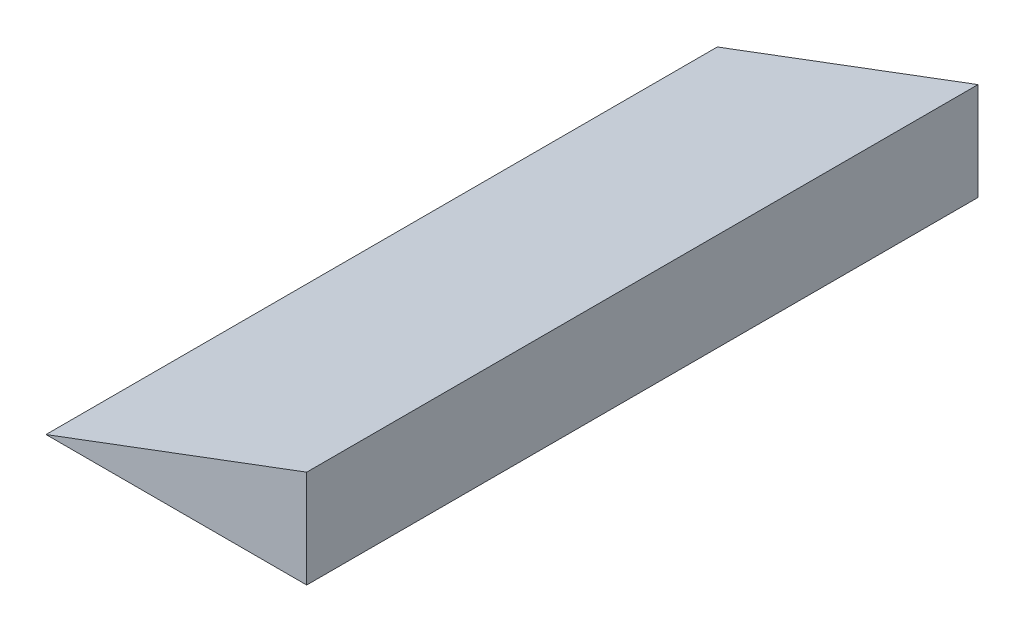
SolidWorks part; units mm, degrees
ref_plane "Front Plane" through (0, 0, 0) normal (0, 0, 1) x (1, 0, 0)
ref_plane "Top Plane" through (0, 0, 0) normal (0, 1, 0) x (1, 0, 0)
ref_plane "Right Plane" through (0, 0, 0) normal (1, 0, 0) x (0, 0, -1)
sketch "Sketch1" plane through (0, 0, 0) normal (0, 0, 1) x (1, 0, 0)
  line L0 (12, 15) -> (-28, 0)
  line L1 (-28, 0) -> (12, 0)
  line L2 (12, 0) -> (12, 15)
  dimension "D1" = 15
  dimension "D2" = 40
  dimension "D3" = 0
  dimension "D4" = 12
extrude "Boss-Extrude1" add sketch "Sketch1" along normal blind 103
sketch "Sketch2" plane through (0, 0, 0) normal (0, -1, 0) x (1, 0, 0)
  line L0 (-28, 103) -> (12, 103) construction
  line L1 (-15, 103) -> (0, 103)
  line L2 (-15, 103) -> (-15, 0)
  line L3 (-15, 0) -> (0, 0)
  line L4 (0, 103) -> (0, 0)
  dimension "D1" = 15
